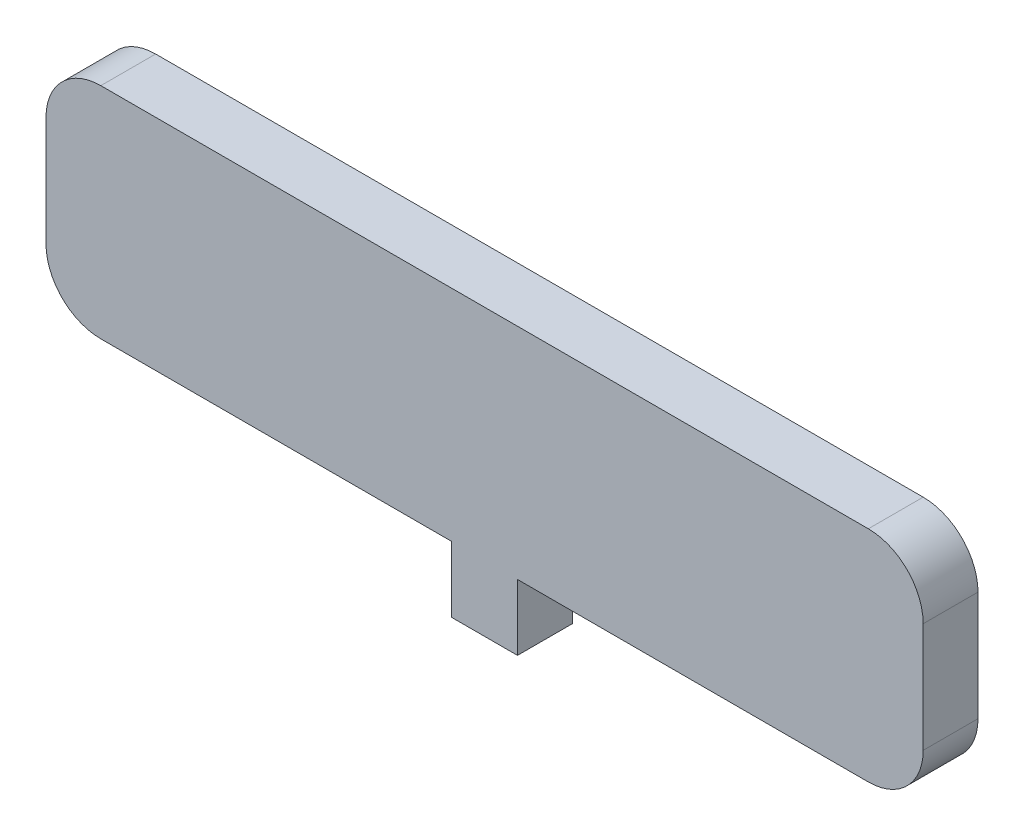
SolidWorks part; units mm, degrees
ref_plane "Front Plane" through (0, 0, 0) normal (0, 0, 1) x (1, 0, 0)
ref_plane "Top Plane" through (0, 0, 0) normal (0, 1, 0) x (1, 0, 0)
ref_plane "Right Plane" through (0, 0, 0) normal (1, 0, 0) x (0, 0, -1)
sketch "Sketch1" plane through (0, 0, 0) normal (0, 0, 1) x (1, 0, 0)
  line L1 (-40, 10) -> (40, 10)
  line L2 (-40, 10) -> (-40, -10)
  line L3 (-40, -10) -> (40, -10)
  line L4 (40, 10) -> (40, -10)
  line L5 (-40, 10) -> (40, -10) construction
  line L6 (-40, -10) -> (40, 10) construction
  point P0 (0, 0)
  dimension "D1" = 80
  dimension "D2" = 20
extrude "Boss-Extrude1" add sketch "Sketch1" along normal blind 5
fillet "Fillet1" radius 5 4 edges at (-40, 10, 2.5) (-40, -10, 2.5) (40, -10, 2.5) (40, 10, 2.5)
shell "Shell1" thickness 2
sketch "Sketch2" plane through (0, -10, 0) normal (0, -1, 0) x (1, 0, 0)
  line L0 (0, 0) -> (0, 5) construction
  line L1 (-35, 0) -> (35, 0) construction
  line L2 (-35, 5) -> (35, 5) construction
  line L4 (3, 0) -> (-3, 0)
  line L5 (3, 0) -> (3, 5)
  line L6 (3, 5) -> (-3, 5)
  line L7 (-3, 0) -> (-3, 5)
  line L8 (3, 0) -> (-3, 5) construction
  line L9 (3, 5) -> (-3, 0) construction
  point P6 (0, 2.5)
  dimension "D1" = 6
extrude "Boss-Extrude2" add sketch "Sketch2" along normal blind 6 contours L4 L7 L6 L5
sketch "Sketch3" plane through (0, -16, 0) normal (0, -1, 0) x (1, 0, 0)
  line L0 (0, 0) -> (0, 5) construction
  line L1 (3, 5) -> (-3, 5) construction
  line L2 (3, 2.5) -> (-3, 2.5) construction
  line L3 (3, 0) -> (3, 5) construction
  line L4 (-3, 0) -> (-3, 5) construction
  circle A0 centre (0, 2.5) radius 1.425
  dimension "D1" = 2.85
extrude "Cut-Extrude1" cut sketch "Sketch3" against normal blind 4
